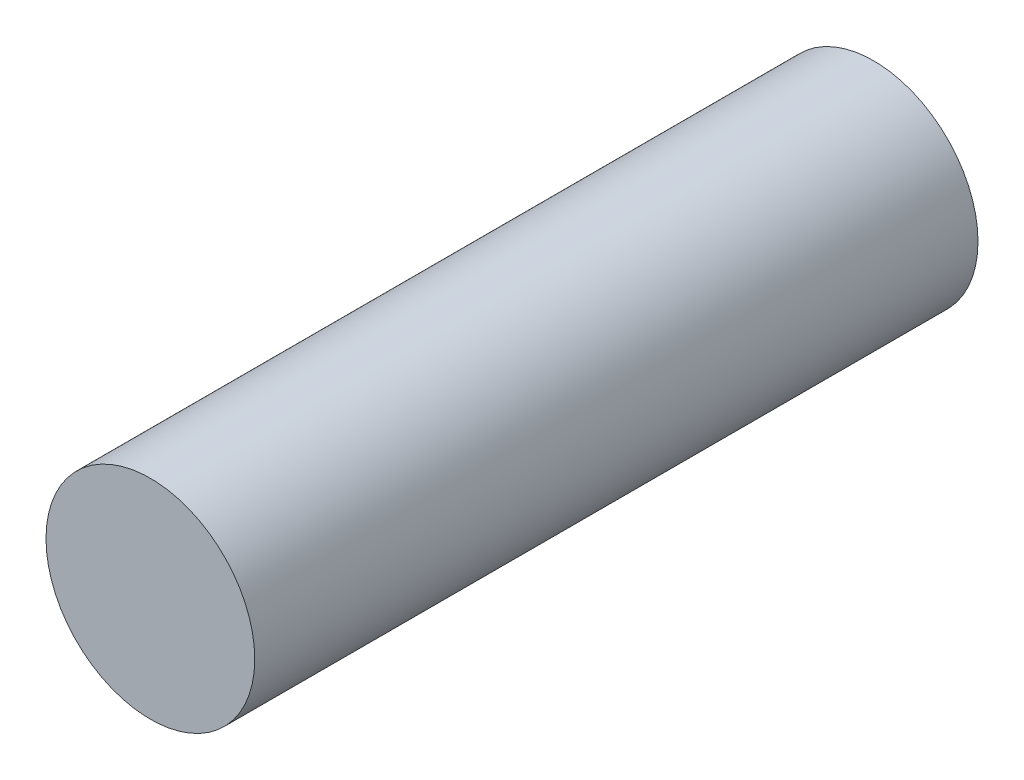
SolidWorks part; units mm, degrees
material "7075-T6 (SN)"
ref_plane "Front Plane" through (0, 0, 0) normal (0, 0, 1) x (1, 0, 0)
ref_plane "Top Plane" through (0, 0, 0) normal (0, 1, 0) x (1, 0, 0)
ref_plane "Right Plane" through (0, 0, 0) normal (1, 0, 0) x (0, 0, -1)
sketch "Sketch1" plane through (0, 0, 0) normal (0, 0, 1) x (1, 0, 0)
  circle A0 centre (0, 0) radius 3.175
  dimension "D1" = 6.35
extrude "Boss-Extrude1" add sketch "Sketch1" along normal blind 22
